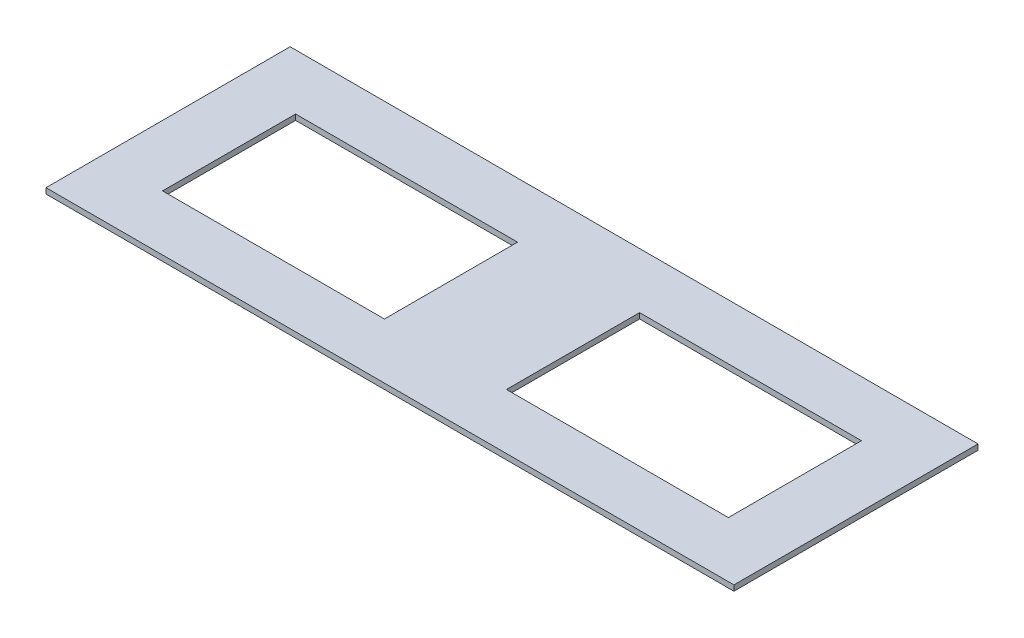
SolidWorks part; units mm, degrees
ref_plane "Front Plane" through (0, 0, 0) normal (0, 0, 1) x (1, 0, 0)
ref_plane "Top Plane" through (0, 0, 0) normal (0, 1, 0) x (1, 0, 0)
ref_plane "Right Plane" through (0, 0, 0) normal (1, 0, 0) x (0, 0, -1)
sketch "Sketch1" plane through (0, 0, 0) normal (0, 1, 0) x (1, 0, 0)
  line L1 (-787.4, -279.4) -> (787.4, -279.4)
  line L2 (-787.4, -279.4) -> (-787.4, 279.4)
  line L3 (-787.4, 279.4) -> (787.4, 279.4)
  line L4 (787.4, -279.4) -> (787.4, 279.4)
  line L5 (-787.4, -279.4) -> (787.4, 279.4) construction
  line L6 (-787.4, 279.4) -> (787.4, -279.4) construction
  line L7 (-647.7, -152.4) -> (-139.7, -152.4)
  line L8 (-647.7, -152.4) -> (-647.7, 152.4)
  line L9 (-647.7, 152.4) -> (-139.7, 152.4)
  line L10 (-139.7, -152.4) -> (-139.7, 152.4)
  line L11 (-647.7, -152.4) -> (-139.7, 152.4) construction
  line L12 (-647.7, 152.4) -> (-139.7, -152.4) construction
  line L13 (139.7, -152.4) -> (647.7, -152.4)
  line L14 (139.7, -152.4) -> (139.7, 152.4)
  line L15 (139.7, 152.4) -> (647.7, 152.4)
  line L16 (647.7, -152.4) -> (647.7, 152.4)
  line L17 (139.7, -152.4) -> (647.7, 152.4) construction
  line L18 (139.7, 152.4) -> (647.7, -152.4) construction
  point P0 (0, 0)
  point P6 (-393.7, 0)
  point P11 (393.7, 0)
  dimension "D1" = 558.8
  dimension "D2" = 1574.8
  dimension "D3" = 508
  dimension "D4" = 508
  dimension "D5" = 304.8
  dimension "D6" = 304.8
  dimension "D7" = 279.4
  dimension "D8" = 279.4
  dimension "D9" = 393.7
  dimension "D10" = 393.7
extrude "Boss-Extrude1" add sketch "Sketch1" along normal blind 12.7
equation "\"D9@Sketch1\"=\"D2@Sketch1\"/4"
equation "\"D10@Sketch1\"=\"D2@Sketch1\"/4"
